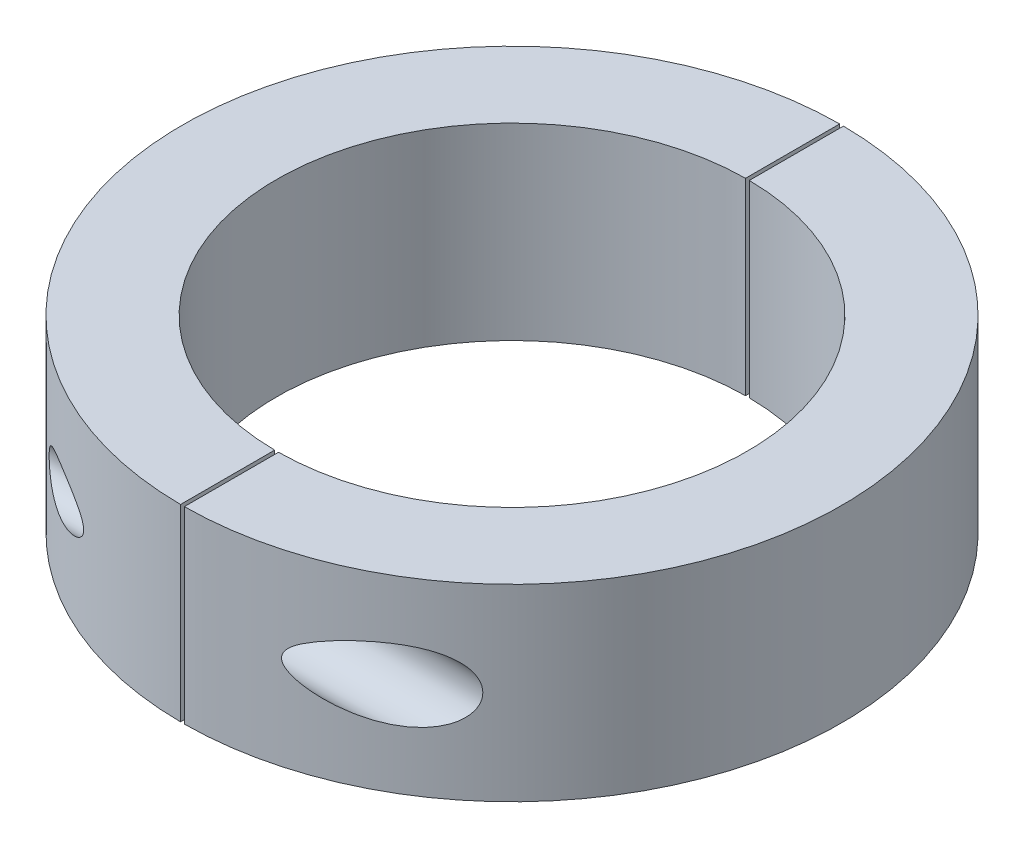
SolidWorks part; units mm, degrees
ref_plane "Front Plane" through (0, 0, 0) normal (0, 0, 1) x (1, 0, 0)
ref_plane "Top Plane" through (0, 0, 0) normal (0, 1, 0) x (1, 0, 0)
ref_plane "Right Plane" through (0, 0, 0) normal (1, 0, 0) x (0, 0, -1)
sketch "Sketch1" plane through (0, 0, 0) normal (0, 1, 0) x (1, 0, 0)
  circle A0 centre (0, 0) radius 44.45
  circle A1 centre (0, 0) radius 31.75
  dimension "D1" = 63.5
  dimension "D2" = 12.7
extrude "Boss-Extrude1" add sketch "Sketch1" along normal blind 25.4
sketch "Sketch2" plane through (0, 25.4, 0) normal (0, 1, 0) x (1, 0, 0)
  line L0 (-0.254, 46.4715) -> (0.254, 46.4715)
  line L1 (-0.254, 46.4715) -> (-0.254, -48.0895)
  line L2 (0.254, 46.4715) -> (0.254, -48.0895)
  line L3 (-0.254, -48.0895) -> (0.254, -48.0895)
extrude "Cut-Extrude1" cut sketch "Sketch2" against normal blind 25.4
sketch "Sketch3" plane through (-0.254, 0, 0) normal (1, 0, 0) x (0, 0, -1)
  line L0 (44.4493, 12.7) -> (-44.4493, 12.7) construction
  line L1 (44.4493, 25.4) -> (44.4493, 0) construction
  line L2 (-44.4493, 0) -> (-44.4493, 25.4) construction
  circle A0 centre (38.0993, 12.7) radius 3.175
  circle A1 centre (-38.0993, 12.7) radius 3.175
  dimension "D3" = 6.35
  dimension "D4" = 6.35
  dimension "D1" = 6.35
  dimension "D2" = 6.35
extrude "Cut-Extrude2" cut sketch "Sketch3" against normal mid plane 58.42
sketch "Sketch4" plane through (0, 0, 0) normal (1, 0, 0) x (0, 0, -1)
  circle A0 centre (38.0993, 12.7) radius 4.7625
  circle A1 centre (-38.0993, 12.7) radius 4.7625
  dimension "D1" = 9.525
  dimension "D2" = 9.525
extrude "Cut-Extrude3" cut sketch "Sketch4" along normal blind 77.47 from offset 6.35
